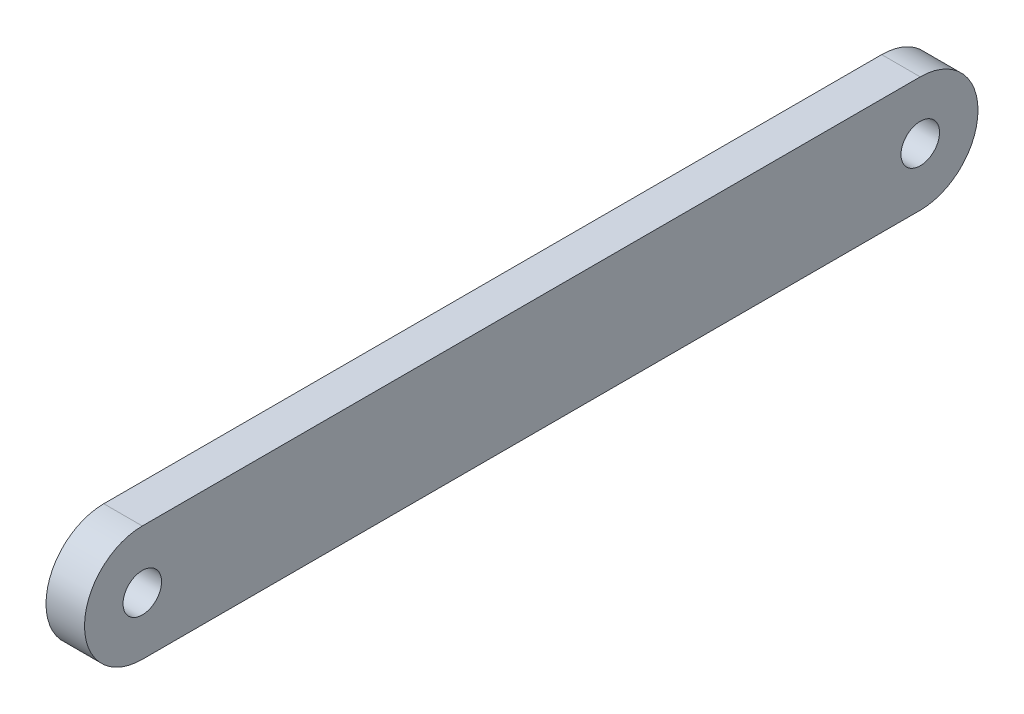
SolidWorks part; units mm, degrees
ref_plane "Front Plane" through (0, 0, 0) normal (0, 0, 1) x (1, 0, 0)
ref_plane "Top Plane" through (0, 0, 0) normal (0, 1, 0) x (1, 0, 0)
ref_plane "Right Plane" through (0, 0, 0) normal (1, 0, 0) x (0, 0, -1)
sketch "Sketch1" plane through (0, 0, 0) normal (1, 0, 0) x (0, 0, -1)
  line L0 (-50, 0) -> (50, 0) construction
  line L1 (-50, 7.5) -> (50, 7.5)
  line L2 (-50, -7.5) -> (50, -7.5)
  line L3 (0, 18.4818) -> (0, -14.0635) construction
  arc A0 (-50, 7.5) -> (-50, -7.5) centre (-50, 0) ccw
  arc A1 (50, -7.5) -> (50, 7.5) centre (50, 0) ccw
  circle A2 centre (-50, 0) radius 2.4
  circle A3 centre (50, 0) radius 2.4
  point P3 (0, 0)
  dimension "D1" = 100
  dimension "D2" = 15
extrude "Boss-Extrude1" add sketch "Sketch1" along normal blind 5
scale "Scale1" scale about centroid uniform scaling yes scale factor 0.8
sketch "Sketch2" plane through (4.5, 0, 0) normal (1, 0, 0) x (0, 0, -1)
  circle A0 centre (-40, 0) radius 2
  circle A1 centre (40, 0) radius 2
extrude "Cut-Extrude1" cut sketch "Sketch2" against normal through all
sketch "Sketch4" plane through (0.5, 0, 0) normal (-1, 0, 0) x (0, 0, 1)
  circle A0 centre (-40, 0) radius 2
extrude "Boss-Extrude2" add sketch "Sketch4" against normal through all
sketch "Sketch6" plane through (0.5, 0, 0) normal (-1, 0, 0) x (0, 0, 1)
  line L0 (40, 0) -> (-40.7821, 0) construction
  line L1 (-40, 6) -> (40, 6) construction
  line L3 (-40.7821, -6) -> (-33.6347, -6)
  line L5 (-40.7821, 6) -> (-33.6347, 6)
  line L6 (-33.6347, -6) -> (-33.6347, 6)
  arc A0 (-40.7821, 6) -> (-40.7821, -6) centre (-40.7821, 0) ccw
extrude "Boss-Extrude3" add sketch "Sketch6" against normal through all
sketch "Sketch7" plane through (0.5, 0, 0) normal (-1, 0, 0) x (0, 0, 1)
  line L0 (40, 0) -> (-40.7876, 0) construction
  circle A0 centre (-40.7876, 0) radius 2
  point P5 (-39.772, -2.0084)
extrude "Cut-Extrude2" cut sketch "Sketch7" against normal through all
